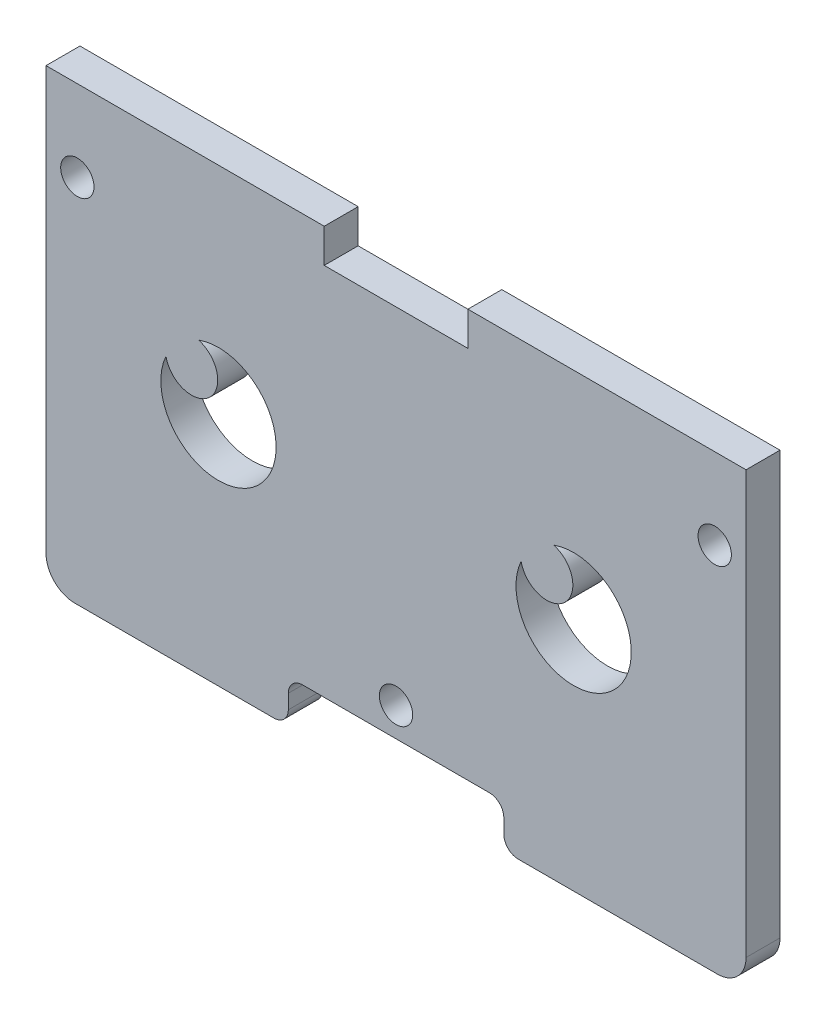
SolidWorks part; units mm, degrees
material "Acrylic (Medium-high impact)"
ref_plane "Front Plane" through (0, 0, 0) normal (0, 0, 1) x (1, 0, 0)
ref_plane "Top Plane" through (0, 0, 0) normal (0, 1, 0) x (1, 0, 0)
ref_plane "Right Plane" through (0, 0, 0) normal (1, 0, 0) x (0, 0, -1)
sketch "Sketch1" plane through (0, 0, 0) normal (0, 0, 1) x (1, 0, 0)
  line L1 (0, 0) -> (61.88, 0)
  line L2 (0, 0) -> (0, 39.878)
  line L3 (0, 39.878) -> (61.88, 39.878)
  line L4 (61.88, 0) -> (61.88, 39.878)
  dimension "D1" = 61.88
  dimension "D2" = 39.878
extrude "Boss-Extrude1" add sketch "Sketch1" along normal blind 3
hole_wizard "#32 (0.116) Diameter Hole1" positions "Sketch5" profile "Sketch2" hole size "#32" standard "ANSI Inch" end condition through all
sketch "Sketch5" plane through (0, 0, 3) normal (0, 0, 1) x (1, 0, 0)
  line L0 (61.88, 39.878) -> (0, 39.878) construction
  line L1 (30.94, 39.878) -> (30.94, 0) construction
  line L2 (0, 0) -> (61.88, 0) construction
  line L3 (0, 39.878) -> (0, 0) construction
  line L4 (61.88, 0) -> (61.88, 39.878) construction
  line L5 (61.88, 39.878) -> (0, 39.878) construction
  point P0 (30.94, 6.374)
  point P19 (59.11, 32.7152)
  point P21 (2.77, 32.7152)
  dimension "D1" = 33.504
  dimension "D4" = 2.77
  dimension "D5" = 2.77
  dimension "D6" = 7.1628
  dimension "D7" = 7.1628
sketch "Sketch2" plane through (30.94, 6.374, 3) normal (1, 0, 0) x (0, -1, 0)
  line L0 (0, 0) -> (0, 3)
  line L1 (0, 3) -> (1.4732, 3)
  line L2 (1.4732, 3) -> (1.4732, 0)
  line L5 (1.4732, 0) -> (0, 0)
  line L11 (0, -6.35) -> (0, 107.95) construction
  dimension "Thru Hole Dia." = 2.9464
  dimension "Thru Hole Depth" = 3
fillet "Fillet1" radius 2.54 2 edges at (0, 0, 1.5) (61.88, 0, 1.5)
sketch "Sketch6" plane through (0, 0, 0) normal (0, 0, -1) x (-1, 0, 0)
  line L0 (-61.88, 39.878) -> (0, 39.878) construction
  line L1 (-37.2928, 39.878) -> (-24.5928, 39.878)
  line L2 (-37.2928, 39.878) -> (-37.2928, 36.878)
  line L3 (-37.2928, 36.878) -> (-24.5928, 36.878)
  line L4 (-24.5928, 39.878) -> (-24.5928, 36.878)
  line L9 (0, 39.878) -> (0, 2.54) construction
  dimension "D1" = 12.7
  dimension "D2" = 3
  dimension "D3" = 24.5928
extrude "Cut-Extrude1" cut sketch "Sketch6" against normal blind 3
sketch "Sketch7" plane through (0, 0, 0) normal (0, 0, -1) x (-1, 0, 0)
  line L0 (-2.54, 0) -> (-59.34, 0) construction
  line L1 (-40.4678, 0) -> (-21.4178, 0)
  line L2 (-40.4678, 0) -> (-40.4678, 3.81)
  line L3 (-40.4678, 3.81) -> (-21.4178, 3.81)
  line L4 (-21.4178, 0) -> (-21.4178, 3.81)
  line L7 (-61.88, 2.54) -> (-61.88, 39.878) construction
  dimension "D1" = 3.81
  dimension "D2" = 19.05
  dimension "D3" = 21.4122
extrude "Cut-Extrude2" cut sketch "Sketch7" against normal through all
sketch "Sketch9" plane through (0, 0, 0) normal (0, 0, -1) x (-1, 0, 0)
  line L0 (-40.4678, 3.81) -> (-38.5628, -0.1194)
  line L1 (-38.5628, -0.1194) -> (-36.6578, 3.81)
  line L2 (-21.4178, 3.81) -> (-40.4678, 3.81) construction
  line L3 (-36.6578, 3.81) -> (-34.7528, -0.1194)
  line L4 (-34.7528, -0.1194) -> (-32.8478, 3.81)
  line L5 (-32.8478, 3.81) -> (-30.9428, -0.1194)
  line L6 (-30.9428, -0.1194) -> (-29.0378, 3.81)
  line L7 (-29.0378, 3.81) -> (-27.1328, -0.1194)
  line L8 (-27.1328, -0.1194) -> (-25.2278, 3.81)
  line L9 (-25.2278, 3.81) -> (-23.3228, -0.1194)
  line L10 (-23.3228, -0.1194) -> (-21.4178, 3.81)
  line L11 (-40.4678, 3.81) -> (-36.6578, 3.81)
  line L12 (-36.6578, 3.81) -> (-32.8478, 3.81)
  line L13 (-32.8478, 3.81) -> (-29.0378, 3.81)
  line L14 (-29.0378, 3.81) -> (-25.2278, 3.81)
  line L15 (-25.2278, 3.81) -> (-21.4178, 3.81)
fillet "Fillet2" radius 1.27 4 edges at (21.4178, 3.81, 1.5) (40.4678, 3.81, 1.5) (21.4178, 0, 1.5) (40.4678, 0, 1.5)
sketch "Sketch10" plane through (0, 0, 0) normal (0, 0, -1) x (-1, 0, 0)
  line L0 (-30.9428, 3.81) -> (-30.9428, 36.878) construction
  line L3 (-22.6878, 3.81) -> (-39.1978, 3.81) construction
  line L4 (-37.2928, 36.878) -> (-24.5928, 36.878) construction
  line L5 (-61.88, 2.54) -> (-61.88, 39.878) construction
  line L6 (-61.88, 39.878) -> (-37.2928, 39.878) construction
  arc A0 (-10.6043, 22.9308) -> (-13.4862, 25.6101) centre (-15.2456, 20.828) cw
  arc A1 (-41.9987, 22.9308) -> (-44.8806, 25.6101) centre (-44.262, 23.3859) cw
  arc A2 (-41.9987, 22.9308) -> (-44.8806, 25.6101) centre (-46.64, 20.828) cw
  arc A3 (-10.6043, 22.9308) -> (-13.4862, 25.6101) centre (-12.8676, 23.3859) cw
  dimension "D1" = 2
  dimension "D3" = 15.24
  dimension "D4" = 19.05
  dimension "D5" = 16.4921
extrude "Cut-Extrude4" cut sketch "Sketch10" against normal blind 3
